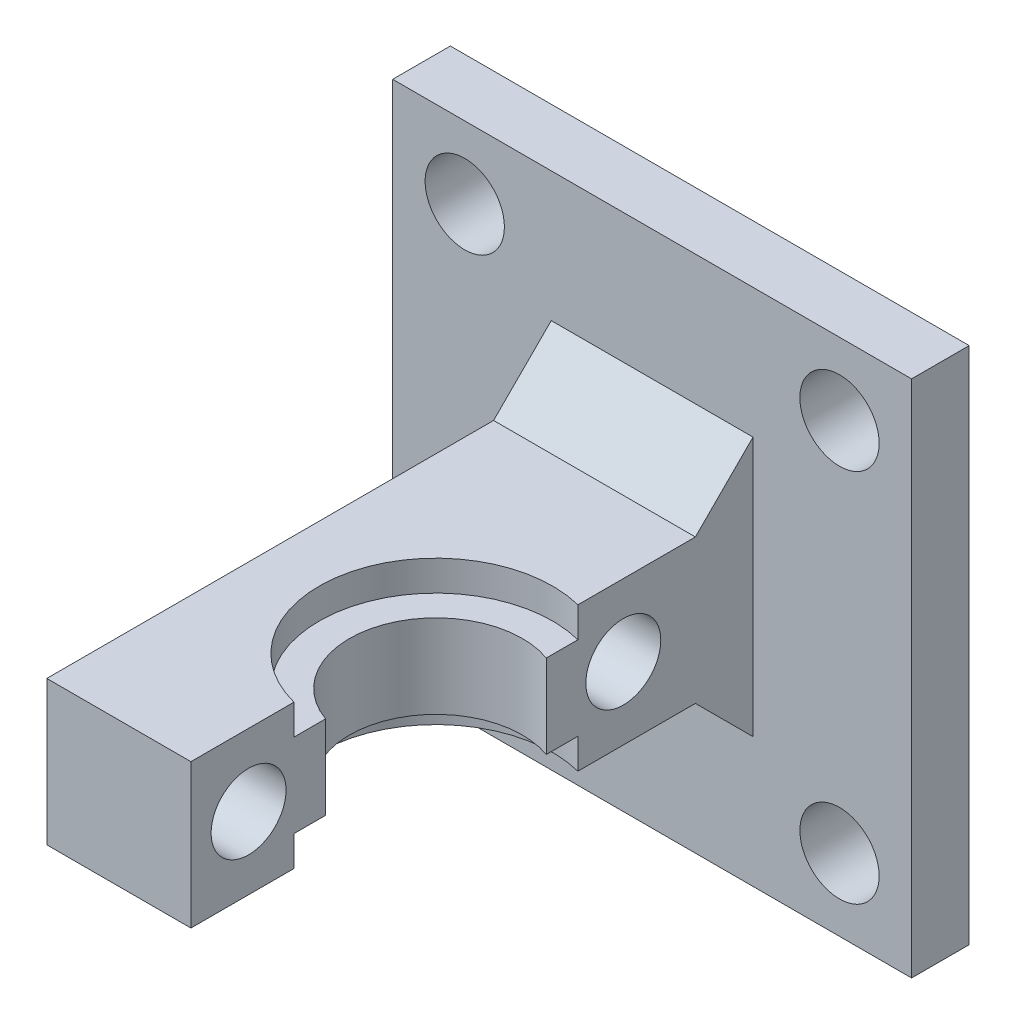
SolidWorks part; units mm, degrees
ref_plane "Front Plane" through (0, 0, 0) normal (0, 0, 1) x (1, 0, 0)
ref_plane "Top Plane" through (0, 0, 0) normal (0, 1, 0) x (1, 0, 0)
ref_plane "Right Plane" through (0, 0, 0) normal (1, 0, 0) x (0, 0, -1)
sketch "Sketch1" plane through (0, 0, 0) normal (0, 0, 1) x (1, 0, 0)
  line L1 (-18, 18) -> (18, 18)
  line L2 (-18, 18) -> (-18, -18)
  line L3 (-18, -18) -> (18, -18)
  line L4 (18, 18) -> (18, -18)
  line L5 (-18, 18) -> (18, -18) construction
  line L6 (-18, -18) -> (18, 18) construction
  point P0 (0, 0)
  dimension "D1" = 36
  dimension "D2" = 36
extrude "Boss-Extrude1" add sketch "Sketch1" along normal blind 4
sketch "Sketch2" plane through (0, 0, 0) normal (0, 0, 1) x (1, 0, 0)
  line L0 (0, 15.4248) -> (0, -21.5401) construction
  line L1 (0, -2.2) -> (0, 2.2) construction
  line L2 (-18.8374, 0) -> (26.7545, 0) construction
  line L3 (2.2, 0) -> (-2.2, 0) construction
  circle A0 centre (-13, 13) radius 2.75
  circle A1 centre (13, 13) radius 2.75
  circle A2 centre (13, -13) radius 2.75
  circle A3 centre (-13, -13) radius 2.75
  dimension "D3" = 5.5
  dimension "D1" = 13
  dimension "D2" = 13
extrude "Cut-Extrude1" cut sketch "Sketch2" along normal up to next
sketch "Sketch3" plane through (0, 0, 0) normal (0, 1, 0) x (1, 0, 0)
  line L0 (-7, -4) -> (-7, -39)
  line L1 (18, -4) -> (-18, -4) construction
  line L2 (-7, -39) -> (3, -39)
  line L3 (0, -19.8) -> (0, 19.8) construction
  line L5 (-7, -4) -> (7, -4)
  line L7 (3, -39) -> (3, -31.8492)
  line L8 (7, -16.1508) -> (7, -4)
  arc A0 (7, -16.1508) -> (3, -31.8492) centre (5, -24) ccw
  dimension "D1" = 8.1
  dimension "D2" = 2
  dimension "D3" = 10
  dimension "D4" = 35
  dimension "D5" = 14
  dimension "D6" = 15
  dimension "D7" = 7
extrude "Boss-Extrude2" add sketch "Sketch3" along normal mid plane 10
chamfer "Chamfer1" distance 4 angle 45 2 edges at (0, -5, 4) (0, 5, 4)
sketch "Sketch4" plane through (0, 0, 0) normal (1, 0, 0) x (0, 0, -1)
  line L0 (19.8, 0) -> (-19.8, 0) construction
  line L1 (-4, 9) -> (-4, -9) construction
  circle A0 centre (-13, 0) radius 2.6
  circle A1 centre (-35, 0) radius 2.6
  dimension "D1" = 5.2
  dimension "D2" = 5.2
  dimension "D3" = 9
  dimension "D4" = 31
extrude "Cut-Extrude2" cut sketch "Sketch4" against normal mid plane 14
sketch "Sketch5" plane through (0, 0, 0) normal (0, 1, 0) x (1, 0, 0)
  line L0 (7, -15.7386) -> (7, -18.3431)
  line L1 (3, -29.6569) -> (3, -32.2614)
  line L2 (0, -19.8) -> (0, 19.8) construction
  arc A0 (7, -18.3431) -> (3, -29.6569) centre (5, -24) ccw
  arc A1 (7, -15.7386) -> (3, -32.2614) centre (5, -24) ccw
  dimension "D1" = 12
  dimension "D2" = 17
  dimension "D3" = 7
  dimension "D4" = 3
extrude "Boss-Extrude3" add sketch "Sketch5" along normal mid plane 5.8
